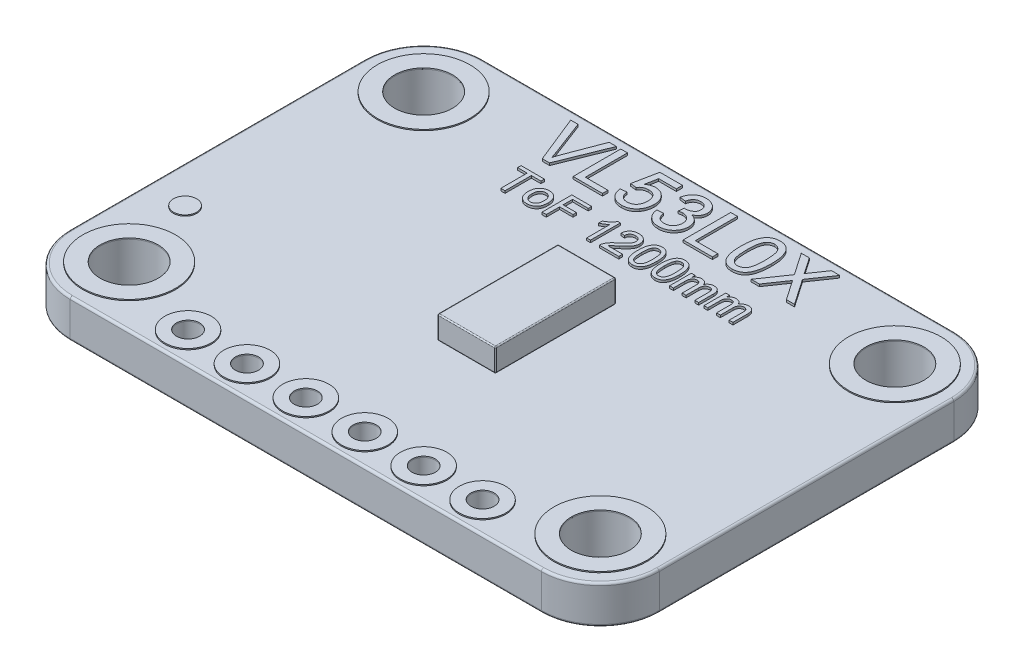
SolidWorks part; units mm, degrees
other "Camera1"
ref_plane "Front Plane" through (0, 0, 0) normal (0, 0, 1) x (1, 0, 0)
ref_plane "Top Plane" through (0, 0, 0) normal (0, 1, 0) x (1, 0, 0)
ref_plane "Right Plane" through (0, 0, 0) normal (1, 0, 0) x (0, 0, -1)
sketch "Sketch1" plane through (0, 0, 0) normal (0, 1, 0) x (1, 0, 0)
  line L0 (12.7, 17.78) -> (12.7, 0) construction
  line L1 (2.54, 0) -> (22.86, 0)
  line L2 (0, 2.54) -> (0, 15.24)
  line L3 (2.54, 17.78) -> (22.86, 17.78)
  line L4 (25.4, 2.54) -> (25.4, 15.24)
  line L5 (0, 8.89) -> (25.4, 8.89) construction
  line L6 (6.35, 1.27) -> (19.685, 1.27) construction
  line L7 (9.525, 19.05) -> (17.145, 19.05) construction
  circle A0 centre (2.54, 2.54) radius 1.25
  arc A1 (22.86, 0) -> (25.4, 2.54) centre (22.86, 2.54) ccw
  arc A2 (22.86, 17.78) -> (25.4, 15.24) centre (22.86, 15.24) cw
  arc A3 (0, 15.24) -> (2.54, 17.78) centre (2.54, 15.24) cw
  arc A4 (2.54, 0) -> (0, 2.54) centre (2.54, 2.54) cw
  circle A5 centre (2.54, 15.24) radius 1.25
  circle A6 centre (22.86, 2.54) radius 1.25
  circle A7 centre (22.86, 15.24) radius 1.25
  circle A8 centre (19.05, 1.27) radius 0.5
  circle A9 centre (16.51, 1.27) radius 0.5
  circle A10 centre (13.97, 1.27) radius 0.5
  circle A11 centre (11.43, 1.27) radius 0.5
  circle A12 centre (8.89, 1.27) radius 0.5
  circle A13 centre (6.35, 1.27) radius 0.5
  point P15 (25.4, 17.78)
  point P18 (0, 17.78)
  point P21 (0, 0)
  dimension "D3" = 2.5
  dimension "D4" = 2.54
  dimension "D5" = 2.54
  dimension "D6" = 2.54
  dimension "D7" = 1
  dimension "D10" = 6.35
  dimension "D1" = 17.78
  dimension "D2" = 25.4
  dimension "D8" = 1.27
  dimension "D11" = 6.35
  dimension "D13" = 19.05
  dimension "D12" = 6
extrude "Boss-Extrude1" add sketch "Sketch1" along normal blind 1.65
sketch "Sketch2" plane through (0, 1.65, 0) normal (0, 1, 0) x (1, 0, 0)
  line L0 (13.335, 11.49) -> (13.335, 6.29) construction
  line L1 (12.085, 11.49) -> (14.585, 11.49)
  line L2 (12.085, 11.49) -> (12.085, 6.29)
  line L3 (12.085, 6.29) -> (14.585, 6.29)
  line L4 (14.585, 11.49) -> (14.585, 6.29)
  line L5 (12.085, 8.89) -> (14.585, 8.89) construction
  line L7 (0, 15.24) -> (0, 2.54) construction
  point P8 (13.335, 8.89)
  point P9 (0, 8.89)
  dimension "D1" = 5.2
  dimension "D2" = 2.5
  dimension "D4" = 13.335
extrude "BNO055_IC" add sketch "Sketch2" along normal blind 1 separate body
fillet "Fillet1" radius 0.1 16 edges at (0.7439, 0, -0.7439) (0, 0, -8.89) (0.7439, 0, -17.0361) (12.7, 0, -17.78) (24.6561, 0, -17.0361) (25.4, 0, -8.89) (24.6561, 0, -0.7439) (0.7439, 1.65, -0.7439) (0, 1.65, -8.89) (0.7439, 1.65, -17.0361) (12.7, 1.65, -17.78) (24.6561, 1.65, -17.0361) (25.4, 1.65, -8.89) (24.6561, 1.65, -0.7439) (12.7, 0, 0) (12.7, 1.65, 0)
fillet "Fillet2" radius 0.05 12 edges at (13.335, 1.65, -11.49) (14.585, 2.15, -11.49) (14.585, 1.65, -8.89) (14.585, 2.15, -6.29) (13.335, 1.65, -6.29) (12.085, 2.15, -11.49) (12.085, 2.15, -6.29) (12.085, 1.65, -8.89) (13.335, 2.65, -11.49) (14.585, 2.65, -8.89) (13.335, 2.65, -6.29) (12.085, 2.65, -8.89)
sketch "Sketch16" plane through (0, 1.65, 0) normal (0, 1, 0) x (1, 0, 0)
  line L0 (2.54, 0) -> (22.86, 0) construction
  line L1 (0, 15.24) -> (0, 2.54) construction
  circle A0 centre (2.54, 2.54) radius 1.25
  circle A1 centre (2.54, 2.54) radius 2
  circle A2 centre (2.54, 15.24) radius 2
  circle A3 centre (2.54, 15.24) radius 1.25
  circle A4 centre (22.86, 15.24) radius 1.25
  circle A5 centre (22.86, 15.24) radius 2
  circle A6 centre (22.86, 2.54) radius 1.25
  circle A7 centre (22.86, 2.54) radius 2
  circle A8 centre (19.05, 1.27) radius 0.5
  circle A9 centre (19.05, 1.27) radius 1
  circle A10 centre (16.51, 1.27) radius 0.5
  circle A11 centre (16.51, 1.27) radius 1
  circle A12 centre (13.97, 1.27) radius 0.5
  circle A13 centre (13.97, 1.27) radius 1
  circle A14 centre (11.43, 1.27) radius 0.5
  circle A15 centre (11.43, 1.27) radius 1
  circle A16 centre (8.89, 1.27) radius 0.5
  circle A17 centre (8.89, 1.27) radius 1
  circle A18 centre (6.35, 1.27) radius 0.5
  circle A19 centre (6.35, 1.27) radius 1
  circle A28 centre (1.651, 5.842) radius 0.5
  dimension "D1" = 4
  dimension "D2" = 2.5
  dimension "D3" = 4
  dimension "D4" = 2.5
  dimension "D5" = 2.5
  dimension "D6" = 4
  dimension "D7" = 2.5
  dimension "D8" = 4
  dimension "D9" = 2
  dimension "D10" = 1
  dimension "D15" = 1
  dimension "D16" = 5.842
  dimension "D17" = 1.651
  dimension "D11" = 6
extrude "Boss-Extrude10" add sketch "Sketch16" along normal blind 0.05 separate body
ref_plane "Plane9" through (0, 0.825, 0) normal (0, 1, 0) x (1, 0, 0)
mirror "Mirror1" about plane through (0, 0.825, 0) normal (0, 1, 0) of "Boss-Extrude10"
sketch "Sketch22" plane through (0, 1.65, 0) normal (0, 1, 0) x (1, 0, 0)
  line L0 (12.7, 17.68) -> (12.7, 0.1) construction
  line L1 (22.86, 17.68) -> (2.54, 17.68) construction
  line L2 (2.54, 0.1) -> (22.86, 0.1) construction
  line L3 (2.54, 15.24) -> (22.86, 15.24) construction
  line L4 (2.54, 13.24) -> (22.86, 13.24) construction
  circle A1 centre (2.54, 15.24) radius 2 construction
  text T0 "VL53L0X\r\n" font "Arial" height in points 8
  text T1 "ToF 1200mm\r\n" font "Arial" height in points 5
  point P9 (12.7, 15.24)
  point P14 (12.7, 13.24)
extrude "Boss-Extrude14" add sketch "Sketch22" along normal blind 0.1
